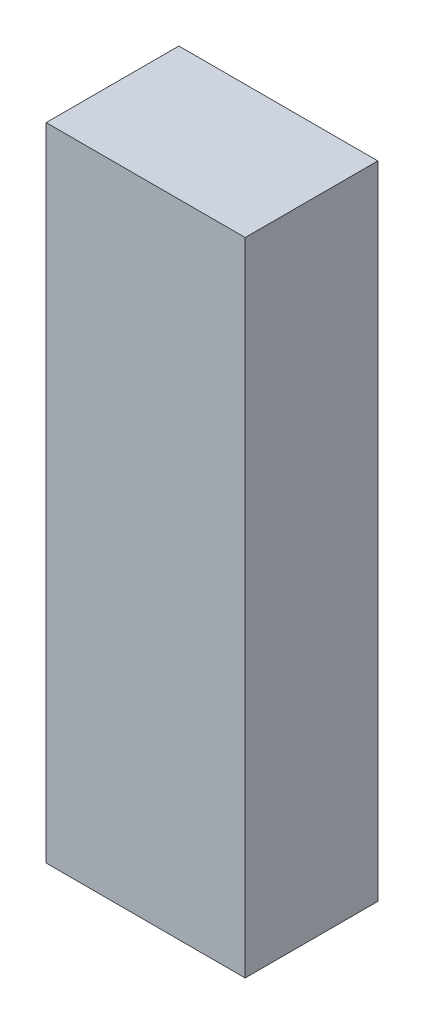
SolidWorks part; units mm, degrees
ref_plane "前视基准面" through (0, 0, 0) normal (0, 0, 1) x (1, 0, 0)
ref_plane "上视基准面" through (0, 0, 0) normal (0, 1, 0) x (1, 0, 0)
ref_plane "右视基准面" through (0, 0, 0) normal (1, 0, 0) x (0, 0, -1)
sketch "草图1" plane through (0, 0, 0) normal (0, 1, 0) x (1, 0, 0)
  line L1 (-22.5, 15) -> (22.5, 15)
  line L2 (-22.5, 15) -> (-22.5, -15)
  line L3 (-22.5, -15) -> (22.5, -15)
  line L4 (22.5, 15) -> (22.5, -15)
  line L5 (-22.5, 15) -> (22.5, -15) construction
  line L6 (-22.5, -15) -> (22.5, 15) construction
  point P0 (0, 0)
  dimension "D1" = 30
  dimension "D2" = 45
extrude "凸台-拉伸1" add sketch "草图1" along normal blind 145
ref_plane "基准面1" through (0, 72.5, 0) normal (0, 1, 0) x (1, 0, 0)
